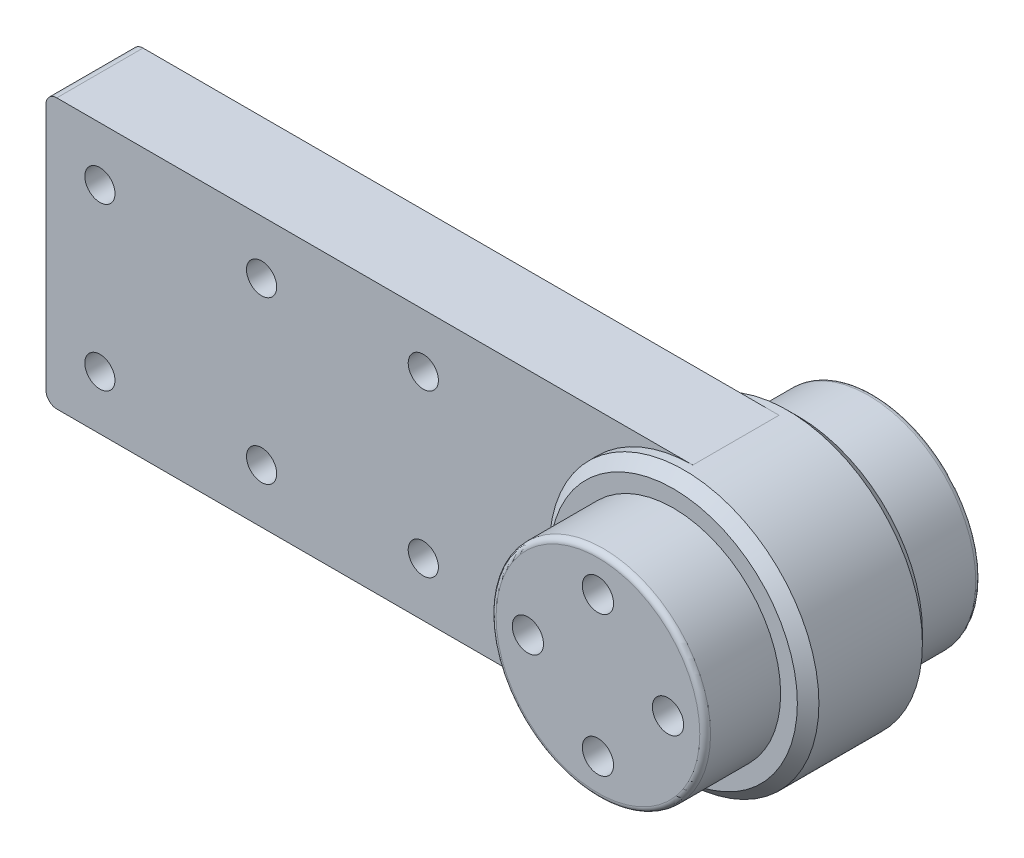
SolidWorks part; units mm, degrees
ref_plane "Front Plane" through (0, 0, 0) normal (0, 0, 1) x (1, 0, 0)
ref_plane "Top Plane" through (0, 0, 0) normal (0, 1, 0) x (1, 0, 0)
ref_plane "Right Plane" through (0, 0, 0) normal (1, 0, 0) x (0, 0, -1)
sketch "Sketch4" plane through (0, 0, 0) normal (0, 1, 0) x (1, 0, 0)
  line L0 (-9.95, -1.8) -> (9.95, -1.8) construction
  line L1 (0, -1.8) -> (0, 0) construction
  line L2 (9.95, -8.8) -> (0, -8.8)
  line L3 (0, -1.8) -> (0, -8.8) construction
  line L4 (9.95, -8.8) -> (9.95, -1.8)
  line L5 (9.95, -1.8) -> (11.5, -1.8)
  line L6 (11.5, -1.8) -> (12.5, -0.8)
  line L7 (12.5, -0.8) -> (12.5, 0)
  line L8 (0, 0) -> (12.5, 0)
  line L9 (0, 0) -> (0, -8.8)
  dimension "D1" = 19.9
  dimension "D2" = 7
  dimension "D3" = 23
  dimension "D4" = 25
  dimension "D5" = 1
  dimension "D6" = 0.8
revolve "Revolve1" add sketch "Sketch4" angle 360 about L9
sketch "Sketch5" plane through (0, 0, 0) normal (0, 0, 1) x (1, 0, 0)
  line L0 (0, 12.5) -> (-60, 12.5)
  line L1 (-60, 12.5) -> (-60, -12.5)
  line L2 (-60, -12.5) -> (0, -12.5)
  circle A0 centre (0, 0) radius 12.5 construction
  arc A1 (0, -12.5) -> (0, 12.5) centre (0, 0) ccw
  dimension "D1" = 60
extrude "Boss-Extrude1" add sketch "Sketch5" against normal blind 4
sketch "Sketch6" plane through (0, 0, 8.8) normal (0, 0, 1) x (1, 0, 0)
  line L0 (0, 0) -> (0, 6.5) construction
  circle A0 centre (0, 6.5) radius 1.45
  circle A1 centre (0, 6.5) radius 3 construction
  circle A2 centre (6.5, 0) radius 1.45
  circle A3 centre (0, -6.5) radius 1.45
  circle A4 centre (-6.5, 0) radius 1.45
  point P14 (0, 0)
  dimension "D1" = 2.9
  dimension "D2" = 6
  dimension "D3" = 6.5
  dimension "D4" = 4
extrude "Cut-Extrude1" cut sketch "Sketch6" against normal through all
mirror "Mirror1" about plane through (0, 0, -4) normal (0, 0, 1) of "Revolve1", "Boss-Extrude1", "Cut-Extrude1"
sketch "Sketch7" plane through (0, 0, 0) normal (0, 0, 1) x (1, 0, 0)
  line L0 (-55, 7.5) -> (-55, -7.5) construction
  line L1 (-60, -12.5) -> (0, -12.5) construction
  line L2 (0, 12.5) -> (-60, 12.5) construction
  line L3 (-60, 12.5) -> (-60, -12.5) construction
  circle A0 centre (-55, 7.5) radius 1.4
  circle A1 centre (-55, -7.5) radius 1.4
  circle A2 centre (-40, 7.5) radius 1.4
  circle A3 centre (-40, -7.5) radius 1.4
  circle A4 centre (-25, 7.5) radius 1.4
  circle A5 centre (-25, -7.5) radius 1.4
  dimension "D4" = 2.8
  dimension "D1" = 5
  dimension "D2" = 5
  dimension "D3" = 5
  dimension "D5" = 3
extrude "Cut-Extrude2" cut sketch "Sketch7" against normal through all
fillet "Fillet1" radius 1 2 edges at (-60, -12.5, -4) (-60, 12.5, -4)
fillet "Fillet2" radius 0.5 2 edges at (-9.95, 0, -16.8) (-9.95, 0, 8.8)
